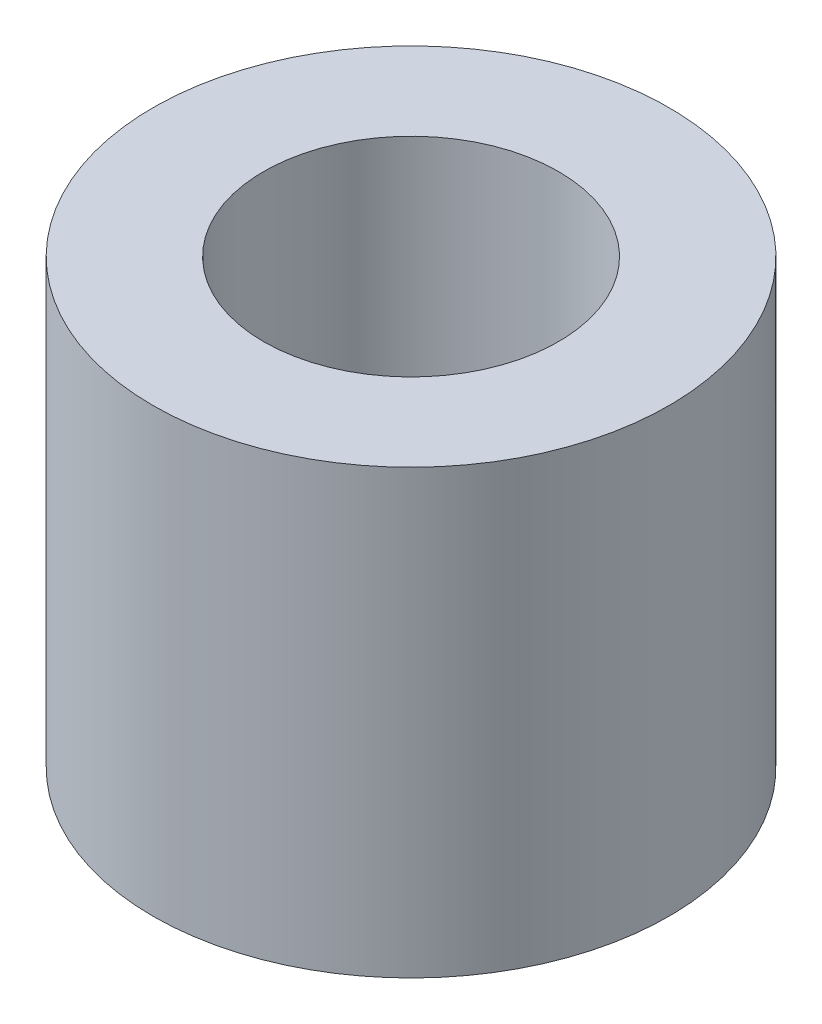
SolidWorks part; units mm, degrees
material "合金钢"
ref_plane "前视基准面" through (0, 0, 0) normal (0, 0, 1) x (1, 0, 0)
ref_plane "上视基准面" through (0, 0, 0) normal (0, 1, 0) x (1, 0, 0)
ref_plane "右视基准面" through (0, 0, 0) normal (1, 0, 0) x (0, 0, -1)
sketch "草图1" plane through (0, 0, 0) normal (0, 1, 0) x (1, 0, 0)
  circle A0 centre (0, 0) radius 1
  circle A1 centre (0, 0) radius 1.75
  dimension "D1" = 2
  dimension "D2" = 3.5
extrude "凸台-拉伸1" add sketch "草图1" along normal blind 3
